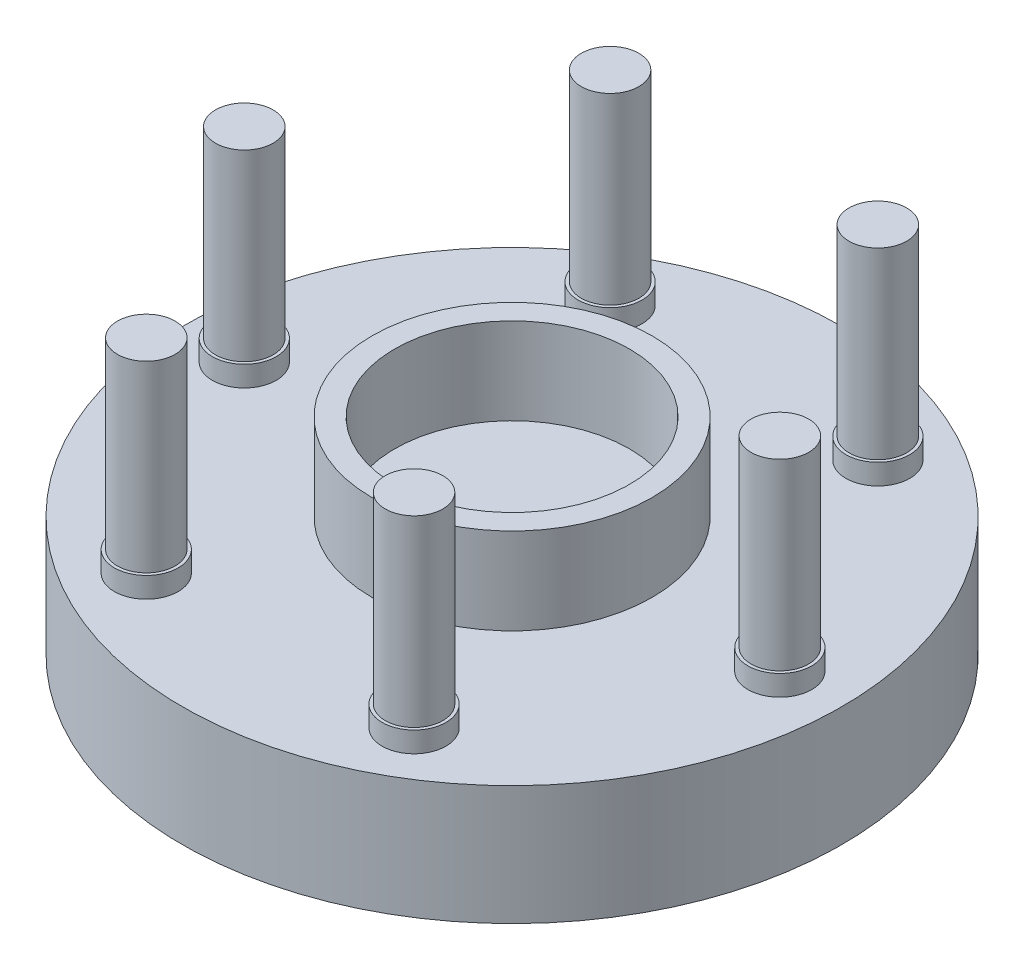
SolidWorks part; units mm, degrees
ref_plane "Front Plane" through (0, 0, 0) normal (0, 0, 1) x (1, 0, 0)
ref_plane "Top Plane" through (0, 0, 0) normal (0, 1, 0) x (1, 0, 0)
ref_plane "Right Plane" through (0, 0, 0) normal (1, 0, 0) x (0, 0, -1)
sketch "Sketch1" plane through (0, 0, 0) normal (0, 1, 0) x (1, 0, 0)
  circle A0 centre (0, 0) radius 80
  dimension "D1" = 160
extrude "Boss-Extrude1" add sketch "Sketch1" along normal blind 29
sketch "Sketch2" plane through (0, 29, 0) normal (0, 1, 0) x (1, 0, 0)
  circle A0 centre (0, 0) radius 28.5
  circle A1 centre (0, 0) radius 34
  dimension "D1" = 57
  dimension "D2" = 68
extrude "Boss-Extrude2" add sketch "Sketch2" along normal blind 21
sketch "Sketch3" plane through (0, 29, 0) normal (0, 1, 0) x (1, 0, 0)
  circle A0 centre (65, 0) radius 7.75
  circle A1 centre (32.5, -56.2917) radius 7.75
  circle A2 centre (-32.5, -56.2917) radius 7.75
  circle A3 centre (-65, 0) radius 7.75
  circle A4 centre (-32.5, 56.2917) radius 7.75
  circle A5 centre (32.5, 56.2917) radius 7.75
  point P15 (0, 0)
  dimension "D1" = 15.5
  dimension "D2" = 65
  dimension "D3" = 6
extrude "Boss-Extrude3" add sketch "Sketch3" along normal blind 5
sketch "Sketch4" plane through (0, 34, 0) normal (0, 1, 0) x (1, 0, 0)
  circle A0 centre (65, 0) radius 7
  circle A1 centre (32.5, -56.2917) radius 7
  circle A2 centre (-32.5, -56.2917) radius 7
  circle A3 centre (-65, 0) radius 7
  circle A4 centre (-32.5, 56.2917) radius 7
  circle A5 centre (32.5, 56.2917) radius 7
  point P15 (0, 0)
  dimension "D1" = 14
  dimension "D2" = 6
extrude "Boss-Extrude4" add sketch "Sketch4" along normal blind 44.5
